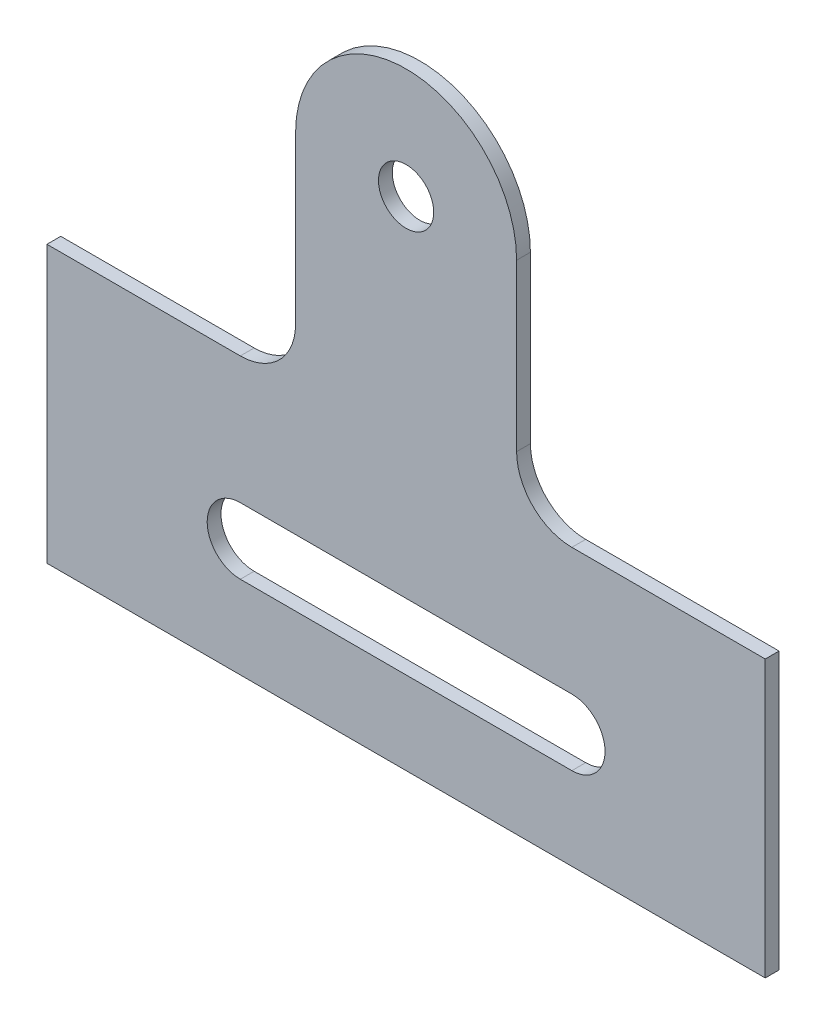
SolidWorks part; units mm, degrees
ref_plane "Ebene vorne" through (0, 0, 0) normal (0, 0, 1) x (1, 0, 0)
ref_plane "Ebene oben" through (0, 0, 0) normal (0, 1, 0) x (1, 0, 0)
ref_plane "Ebene rechts" through (0, 0, 0) normal (1, 0, 0) x (0, 0, -1)
sketch "Skizze1" plane through (0, 0, 0) normal (0, 0, 1) x (1, 0, 0)
  line L0 (0, 0) -> (0, 42) construction
  line L1 (-65, 0) -> (65, 0)
  line L2 (65, 0) -> (65, 50)
  line L3 (65, 50) -> (30, 50)
  line L4 (20, 60) -> (20, 90)
  line L10 (-20, 60) -> (-20, 90)
  line L11 (-65, 50) -> (-30, 50)
  line L12 (-65, 0) -> (-65, 50)
  line L13 (0, 42) -> (0, 139.9347) construction
  line L14 (-30, 21) -> (30, 21) construction
  line L15 (-30, 27) -> (30, 27)
  line L16 (-30, 15) -> (30, 15)
  arc A0 (20, 60) -> (30, 50) centre (30, 60) ccw
  arc A1 (-20, 60) -> (-30, 50) centre (-30, 60) cw
  arc A4 (-30, 27) -> (-30, 15) centre (-30, 21) ccw
  arc A5 (30, 15) -> (30, 27) centre (30, 21) ccw
  arc A6 (20, 90) -> (-20, 90) centre (0, 90) ccw
  circle A7 centre (0, 90) radius 5
  point P7 (0, 110)
  point P12 (0, 21)
  point P18 (0, 26.5956)
  point P19 (0, 14.5956)
  point P20 (0, 110)
  point P27 (-29.4813, 15)
  dimension "D1" = 10
  dimension "D8" = 10
  dimension "D10" = 15
  dimension "D2" = 130
  dimension "D3" = 110
  dimension "D4" = 40
  dimension "D5" = 50
  dimension "D6" = 12
  dimension "D7" = 60
extrude "Aufsatz-Linear austragen1" add sketch "Skizze1" along normal blind 2.5
